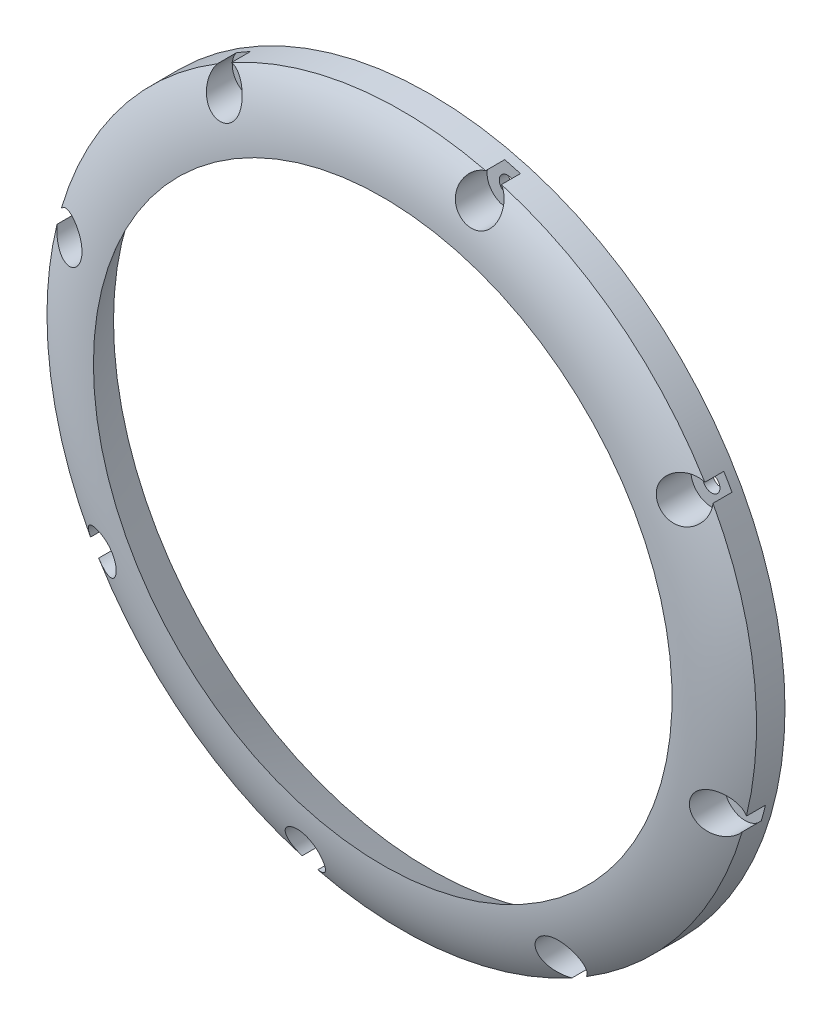
SolidWorks part; units mm, degrees
material "PUR"
ref_plane "Front Plane" through (0, 0, 0) normal (0, 0, 1) x (1, 0, 0)
ref_plane "Top Plane" through (0, 0, 0) normal (0, 1, 0) x (1, 0, 0)
ref_plane "Right Plane" through (0, 0, 0) normal (1, 0, 0) x (0, 0, -1)
sketch "Sketch1" plane through (0, 0, 0) normal (0, 0, 1) x (1, 0, 0)
  circle A0 centre (0, 0) radius 100 construction
  circle A1 centre (0, 0) radius 100
  circle A2 centre (0, 0) radius 112
  arc A3 (111.914, 4.3889) -> (-77.2845, 81.0624) centre (0, 0) ccw construction
sketch "Sketch2" plane through (0, 0, 0) normal (0, 1, 0) x (1, 0, 0)
  line L0 (-112, 0) -> (112, 0) construction
  line L1 (-100, 0) -> (100, 0) construction
  line L2 (-112, 0) -> (112, 0) construction
  line L3 (-100, 0) -> (100, 0) construction
  line L4 (-100, 0) -> (-112, 0)
  line L5 (-100, 0) -> (-91.3397, -15)
  line L6 (0, 0) -> (0, -15) construction
  line L7 (-112, 0) -> (-112, -9)
  line L8 (-91.3397, -15) -> (0, -15) construction
  arc A0 (-91.3397, -15) -> (-112, -9) centre (-91.3397, 23.5705) cw
  dimension "D1" = 60
  dimension "D2" = 9
  dimension "D3" = 15
revolve "Revolve1" add sketch "Sketch2" angle 360 about L6
sketch "Sketch3" plane through (0, 0, 0) normal (0, 0, -1) x (-1, 0, 0)
  circle A0 centre (-102.3881, -27.4348) radius 2.65 construction
  circle A1 centre (-102.3881, -27.4348) radius 2.65
extrude "Cut-Extrude1" cut sketch "Sketch3" against normal through all
sketch "Sketch4" plane through (0, 0, 0) normal (0, 0, -1) x (-1, 0, 0)
  circle A0 centre (-102.3881, -27.4348) radius 6.5
  dimension "D1" = 13
extrude "Cut-Extrude2" cut sketch "Sketch4" against normal through all from offset 3 offset against normal yes
pattern_circular "CirPattern1" count 8 over 360 about axis through (0, 0, 0) along (0, 0, 1) of "Cut-Extrude1", "Cut-Extrude2"
